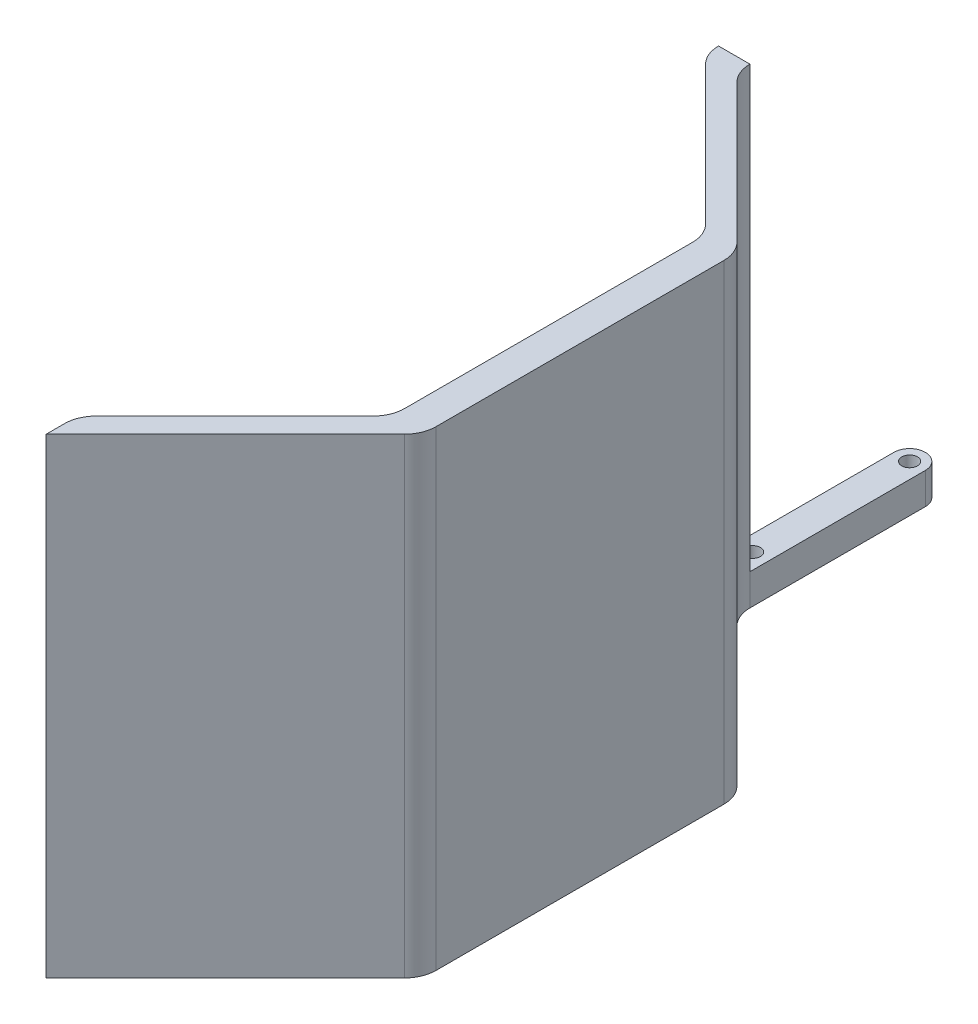
SolidWorks part; units mm, degrees
ref_plane "前视基准面" through (0, 0, 0) normal (0, 0, 1) x (1, 0, 0)
ref_plane "上视基准面" through (0, 0, 0) normal (0, 1, 0) x (1, 0, 0)
ref_plane "右视基准面" through (0, 0, 0) normal (1, 0, 0) x (0, 0, -1)
sketch "草图1" plane through (0, 0, 0) normal (0, 1, 0) x (1, 0, 0)
  line L0 (0, 0) -> (0, 100)
  line L1 (78.9294, 45.9986) -> (78.9294, -4.0014) construction
  line L2 (83.9294, 45.9986) -> (83.9294, -4.0014)
  line L3 (73.9294, 45.9986) -> (73.9294, -4.0014)
  line L4 (73.9294, -4.0014) -> (73.9294, -9.8592)
  line L5 (83.9294, -4.0014) -> (83.9294, -9.8592)
  line L8 (76.8583, -16.9303) -> (121.0004, -61.0725)
  line L9 (123.9294, -68.1435) -> (123.9294, -159.8592)
  line L12 (121.0004, -166.9303) -> (76.8583, -211.0725)
  line L13 (86.8583, -16.9303) -> (131.0004, -61.0725)
  line L14 (133.9294, -68.1435) -> (133.9294, -159.8592)
  line L15 (131.0004, -166.9303) -> (73.9294, -224.0014)
  line L16 (73.9294, -224.0014) -> (73.9294, -218.1435)
  line L17 (-73.9294, -224.0014) -> (-73.9294, -218.1435)
  line L18 (-121.0004, -166.9303) -> (-76.8583, -211.0725)
  line L19 (-131.0004, -166.9303) -> (-73.9294, -224.0014)
  line L20 (-133.9294, -68.1435) -> (-133.9294, -159.8592)
  line L21 (-123.9294, -68.1435) -> (-123.9294, -159.8592)
  line L22 (-86.8583, -16.9303) -> (-131.0004, -61.0725)
  line L23 (-76.8583, -16.9303) -> (-121.0004, -61.0725)
  line L24 (-83.9294, -4.0014) -> (-83.9294, -9.8592)
  line L25 (-73.9294, -4.0014) -> (-73.9294, -9.8592)
  line L26 (-83.9294, 45.9986) -> (-83.9294, -4.0014)
  line L27 (-73.9294, 45.9986) -> (-73.9294, -4.0014)
  arc A0 (83.9294, 45.9986) -> (73.9294, 45.9986) centre (78.9294, 45.9986) ccw
  arc A2 (73.9294, -218.1435) -> (76.8583, -211.0725) centre (83.9294, -218.1435) cw
  arc A3 (133.9294, -159.8592) -> (131.0004, -166.9303) centre (123.9294, -159.8592) cw
  arc A4 (123.9294, -159.8592) -> (121.0004, -166.9303) centre (113.9294, -159.8592) cw
  arc A5 (131.0004, -61.0725) -> (133.9294, -68.1435) centre (123.9294, -68.1435) cw
  arc A6 (123.9294, -68.1435) -> (121.0004, -61.0725) centre (113.9294, -68.1435) ccw
  arc A7 (86.8583, -16.9303) -> (83.9294, -9.8592) centre (93.9294, -9.8592) cw
  arc A8 (76.8583, -16.9303) -> (73.9294, -9.8592) centre (83.9294, -9.8592) cw
  arc A9 (-73.9294, -218.1435) -> (-76.8583, -211.0725) centre (-83.9294, -218.1435) ccw
  arc A10 (-133.9294, -159.8592) -> (-131.0004, -166.9303) centre (-123.9294, -159.8592) ccw
  arc A11 (-123.9294, -159.8592) -> (-121.0004, -166.9303) centre (-113.9294, -159.8592) ccw
  arc A12 (-131.0004, -61.0725) -> (-133.9294, -68.1435) centre (-123.9294, -68.1435) ccw
  arc A13 (-123.9294, -68.1435) -> (-121.0004, -61.0725) centre (-113.9294, -68.1435) cw
  arc A14 (-86.8583, -16.9303) -> (-83.9294, -9.8592) centre (-93.9294, -9.8592) ccw
  arc A15 (-76.8583, -16.9303) -> (-73.9294, -9.8592) centre (-83.9294, -9.8592) ccw
  arc A16 (-83.9294, 45.9986) -> (-73.9294, 45.9986) centre (-78.9294, 45.9986) cw
  point P5 (78.9294, 20.9986)
  dimension "D1" = 10
extrude "凸台-拉伸1" add sketch "草图1" along normal blind 150
sketch "草图3" plane through (0, 150, 0) normal (0, 1, 0) x (1, 0, 0)
  line L0 (83.9294, -9.8592) -> (73.9294, -9.8592)
  line L1 (73.9294, -9.8592) -> (73.9294, 45.9986)
  line L2 (83.9294, 45.9986) -> (83.9294, -9.8592)
  arc A0 (83.9294, 45.9986) -> (73.9294, 45.9986) centre (78.9294, 45.9986) ccw
extrude "切除-拉伸1" cut sketch "草图3" against normal blind 140
sketch "草图5" plane through (0, 0, 0) normal (0, -1, 0) x (1, 0, 0)
  circle A0 centre (78.9294, -45.9986) radius 2.5
  circle A1 centre (78.9294, 4.0014) radius 2.5
extrude "切除-拉伸2" cut sketch "草图5" against normal through all
